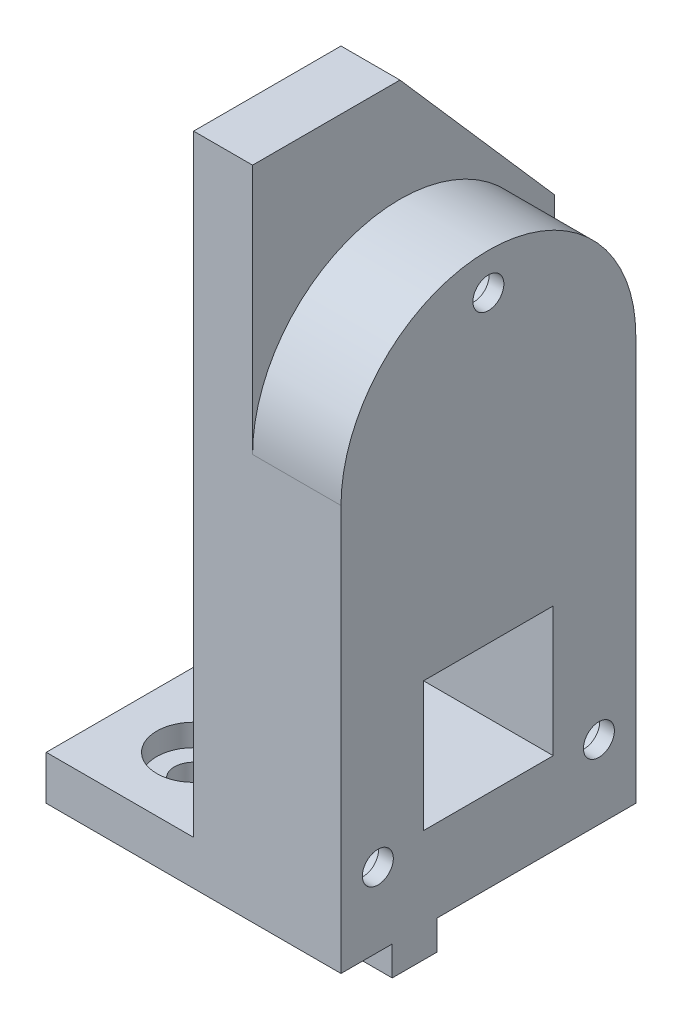
SolidWorks part; units mm, degrees
ref_plane "前视基准面" through (0, 0, 0) normal (0, 0, 1) x (1, 0, 0)
ref_plane "上视基准面" through (0, 0, 0) normal (0, 1, 0) x (1, 0, 0)
ref_plane "右视基准面" through (0, 0, 0) normal (1, 0, 0) x (0, 0, -1)
other "Configuration Table"
sketch "草图1" plane through (0, 0, 0) normal (0, 1, 0) x (1, 0, 0)
  line L0 (0, -30) -> (0, -25)
  line L2 (0, 30) -> (10, 30)
  line L3 (0, -30) -> (-10, -30)
  line L4 (0, 30) -> (0, 25)
  line L5 (-10, -30) -> (10, -30)
  line L6 (-10, -30) -> (-10, 30)
  line L7 (-10, 30) -> (10, 30)
  line L8 (10, -30) -> (10, 30)
  circle A0 centre (0, 25) radius 2.6
  circle A1 centre (0, -25) radius 2.6
extrude "凸台-拉伸1" add sketch "草图1" along normal blind 6
sketch "草图2" plane through (0, 0, 0) normal (0, -1, 0) x (1, 0, 0)
  line L0 (0, 25) -> (3.05, 25)
  line L1 (3.05, 25) -> (3.05, 30)
  line L2 (-10, 30) -> (10, 30) construction
  line L3 (0, 25) -> (-3.05, 25)
  line L4 (-3.05, 25) -> (-3.05, 28.05)
  line L5 (-3.05, 25) -> (-3.05, 21.95)
  line L6 (-3.05, 28.05) -> (3.05, 28.05)
  line L7 (-3.05, 28.05) -> (-3.05, 30)
  line L8 (-3.05, 30) -> (3.05, 30)
  line L9 (3.05, 28.05) -> (3.05, 30)
  line L10 (0, -25) -> (3.05, -25)
  line L11 (0, -25) -> (-2.9939, -25)
  line L12 (-2.9939, -25) -> (-2.9939, -28.05)
  line L13 (3.05, -25) -> (3.05, -21.95)
  line L14 (3.05, -25) -> (3.05, -30)
  line L15 (-10, -30) -> (10, -30) construction
  line L17 (-2.9939, -28.05) -> (3.05, -28.05)
  line L18 (-2.9939, -28.05) -> (-2.9939, -30)
  line L19 (-2.9939, -30) -> (3.05, -30)
  line L20 (3.05, -28.05) -> (3.05, -30)
  line L21 (3.05, -21.95) -> (-3.05, -21.95)
  line L22 (3.05, -21.95) -> (3.05, 21.95)
  line L23 (3.05, 21.95) -> (-3.05, 21.95)
  line L24 (-3.05, -21.95) -> (-3.05, 21.95)
  line M13 (-10, -30) -> (10, -30)
  line M15 (10, 30) -> (-10, 30)
extrude "凸台-拉伸2" add sketch "草图2" along normal blind 4 contours L24 L21 L22 L23 | L7 L6 L1 M15 | L17 L18 L14 M13
sketch "草图3" plane through (0, 6, 0) normal (0, 1, 0) x (1, 0, 0)
  circle A0 centre (0, -25) radius 4.9
  circle A1 centre (0, 25) radius 4.9
extrude "切除-拉伸3" cut sketch "草图3" against normal blind 3
sketch "草图4" plane through (0, 6, 0) normal (0, 1, 0) x (1, 0, 0)
  line L0 (-10, 30) -> (-10, 20)
  line L1 (-10, -30) -> (-10, 30) construction
  line L2 (10, -30) -> (10, -20)
  line L3 (10, -30) -> (10, 30) construction
  line L5 (-10, 20) -> (10, 20)
  line L6 (-10, 20) -> (-10, -20)
  line L7 (-10, -20) -> (10, -20)
  line L8 (10, 20) -> (10, -20)
extrude "凸台-拉伸3" add sketch "草图4" along normal blind 69 contours L6 L5 L8 L7
sketch "草图5" plane through (-10, 0, 0) normal (-1, 0, 0) x (0, 0, 1)
  line L1 (0, 11.2) -> (8.8, 11.2)
  line L5 (0, 28.8) -> (-8.8, 28.8)
  line L7 (-8.8, 28.8) -> (8.8, 28.8)
  line L8 (-8.8, 28.8) -> (-8.8, 11.2)
  line L9 (-8.8, 11.2) -> (8.8, 11.2)
  line L10 (8.8, 28.8) -> (8.8, 11.2)
extrude "切除-拉伸4" cut sketch "草图5" against normal blind 75 contours L10 L7 L5 L8 L9 L1
sketch "草图6" plane through (-10, 0, 0) normal (-1, 0, 0) x (0, 0, 1)
  line L0 (0, 0) -> (0, 70)
  line L1 (30, 0) -> (-30, 0) construction
  line L4 (0, 10) -> (15, 10)
  line L6 (0, 10) -> (-15, 10)
  circle A0 centre (0, 70) radius 2.1
  circle A1 centre (-15, 10) radius 2.1
  circle A2 centre (15, 10) radius 2.1
extrude "切除-拉伸5" cut sketch "草图6" against normal blind 75
sketch "草图7" plane through (-10, 0, 0) normal (-1, 0, 0) x (0, 0, 1)
  line L0 (0, 75) -> (0, 55)
  line L2 (-20, 75) -> (20, 75) construction
  line L3 (-20, 75) -> (-20, 6) construction
  line L4 (-20, 55) -> (-20, 75)
  line L5 (-20, 75) -> (0, 75)
  line L6 (20, 55) -> (20, 75)
  line L7 (20, 75) -> (0, 75)
  arc A1 (-20, 55) -> (20, 55) centre (0, 55) cw
  line M9 (20, 6) -> (20, 75)
  line M10 (20, 75) -> (-20, 75)
  line M11 (-20, 75) -> (-20, 6)
extrude "切除-拉伸6" cut sketch "草图7" against normal blind 75 contours A1 M11 M10 | A1 M10 M9
sketch "草图13" plane through (-10, 0, 0) normal (-1, 0, 0) x (0, 0, 1)
  circle A0 centre (-15, 10) radius 3.5
  circle A1 centre (15, 10) radius 3.5
extrude "切除-拉伸8" cut sketch "草图13" against normal blind 3 contours A0 | A1
sketch "草图14" plane through (5, 0, 0) normal (-1, 0, 0) x (0, 0, 1)
  circle A0 centre (0, 70) radius 3.5
extrude "切除-拉伸9" cut sketch "草图14" against normal blind 3
sketch "草图15" plane through (0, -4, 0) normal (0, -1, 0) x (-1, 0, 0)
  line L1 (3.05, -28.05) -> (-3.05, -28.05)
  line L2 (3.05, -28.05) -> (3.05, -30)
  line L3 (3.05, -30) -> (-3.05, -30)
  line L4 (-3.05, -28.05) -> (-3.05, -30)
  line L5 (2.9939, 28.05) -> (-3.05, 28.05)
  line L6 (2.9939, 28.05) -> (2.9939, 30)
  line L7 (2.9939, 30) -> (-3.05, 30)
  line L8 (-3.05, 28.05) -> (-3.05, 30)
extrude "切除-拉伸10" cut sketch "草图15" against normal blind 4
sketch "草图24" plane through (-10, 0, 0) normal (-1, 0, 0) x (0, 0, 1)
  circle A0 centre (-15, 10) radius 3.5
  circle A1 centre (15, 10) radius 3.5
extrude "切除-拉伸14" cut sketch "草图24" against normal blind 15 contours A0 | A1
sketch "草图25" plane through (-10, 0, 0) normal (-1, 0, 0) x (0, 0, 1)
  circle A0 centre (0, 70) radius 3.5
extrude "切除-拉伸15" cut sketch "草图25" against normal blind 15
sketch "草图26" plane through (0, -4, 0) normal (0, -1, 0) x (-1, 0, 0)
  line L1 (3.05, -21.95) -> (-3.05, -21.95)
  line L2 (3.05, -21.95) -> (3.05, 21.95)
  line L3 (3.05, 21.95) -> (-3.05, 21.95)
  line L4 (-3.05, -21.95) -> (-3.05, 21.95)
extrude "切除-拉伸16" cut sketch "草图26" against normal blind 4 contours L2 L1 L4 L3
sketch "草图27" plane through (0, 6, 0) normal (0, 1, 0) x (1, 0, 0)
  line L1 (-10, 30) -> (10, 30)
  line L2 (-10, 30) -> (-10, 20)
  line L3 (-10, 20) -> (10, 20)
  line L4 (10, 30) -> (10, 20)
  line L5 (10, -30) -> (-10, -30)
  line L6 (10, -30) -> (10, -20)
  line L7 (10, -20) -> (-10, -20)
  line L8 (-10, -30) -> (-10, -20)
extrude "切除-拉伸17" cut sketch "草图27" against normal blind 10
sketch "草图28" plane through (0, 0, 0) normal (0, -1, 0) x (1, 0, 0)
  line L0 (10, 20) -> (10, -20) construction
  line L7 (10, 10) -> (10, 13.05)
  line L9 (-10, 10) -> (-10, 6.95)
  line L11 (-10, 6.95) -> (10, 6.95)
  line L12 (-10, 6.95) -> (-10, 13.05)
  line L13 (-10, 13.05) -> (10, 13.05)
  line L14 (10, 6.95) -> (10, 13.05)
  line M12 (-10, 20) -> (-10, -20)
  line M14 (10, -20) -> (10, 20)
extrude "凸台-拉伸4" add sketch "草图28" along normal blind 4 contours L13 L11 M12 M14
sketch "草图29" plane through (-10, 0, 0) normal (-1, 0, 0) x (0, 0, 1)
  circle A0 centre (0, 70) radius 3.5
  circle A1 centre (15, 10) radius 3.5
  circle A2 centre (-15, 10) radius 3.5
extrude "切除-拉伸18" cut sketch "草图29" against normal blind 18
sketch "草图30" plane through (-10, 0, 0) normal (-1, 0, 0) x (0, 0, 1)
  line L0 (20, 55) -> (20, 89)
  line L1 (20, 89) -> (0, 89)
  line L2 (-20, 0) -> (-21, 0)
  line L3 (-21, 0) -> (-21, 65)
  line L4 (-21, 65) -> (0, 89)
  line L5 (-20, 0) -> (-20, 55)
  arc A0 (-20, 55) -> (20, 55) centre (0, 55) cw
extrude "凸台-拉伸5" add sketch "草图30" against normal blind 8 contours L0 L1 L4 L3 L2 L5 A0
sketch "草图31" plane through (0, 0, 0) normal (0, -1, 0) x (1, 0, 0)
  line L0 (-10, 20) -> (-10, 0)
  line L1 (-10, 6.95) -> (-10, -21) construction
  line L2 (-10, 0) -> (-30, 0)
  line L3 (-30, 0) -> (-30, 20)
  line L4 (-30, 20) -> (-10, 20)
extrude "凸台-拉伸6" add sketch "草图31" against normal blind 3 contours L4 L0 L2 L3
sketch "草图32" plane through (0, 0, 0) normal (0, -1, 0) x (-1, 0, 0)
  line L0 (30, -20) -> (10, 0)
  circle A0 centre (20, -10) radius 2.6
extrude "切除-拉伸19" cut sketch "草图32" against normal blind 6 contours L0 A0 | L0 A0
sketch "草图33" plane through (0, 3, 0) normal (0, 1, 0) x (1, 0, 0)
  line L0 (-10, -20) -> (-10, 0) construction
  line L1 (-30, 0) -> (-10, 0)
  line L2 (-30, 0) -> (-30, -20)
  line L3 (-30, -20) -> (-10, -20)
  line L4 (-10, 0) -> (-10, -20)
  line L5 (-2, -20) -> (-10, -20) construction
  circle A0 centre (-20, -10) radius 5
extrude "凸台-拉伸7" add sketch "草图33" along normal blind 3 contours L2 L1 L4 L3 | A0
